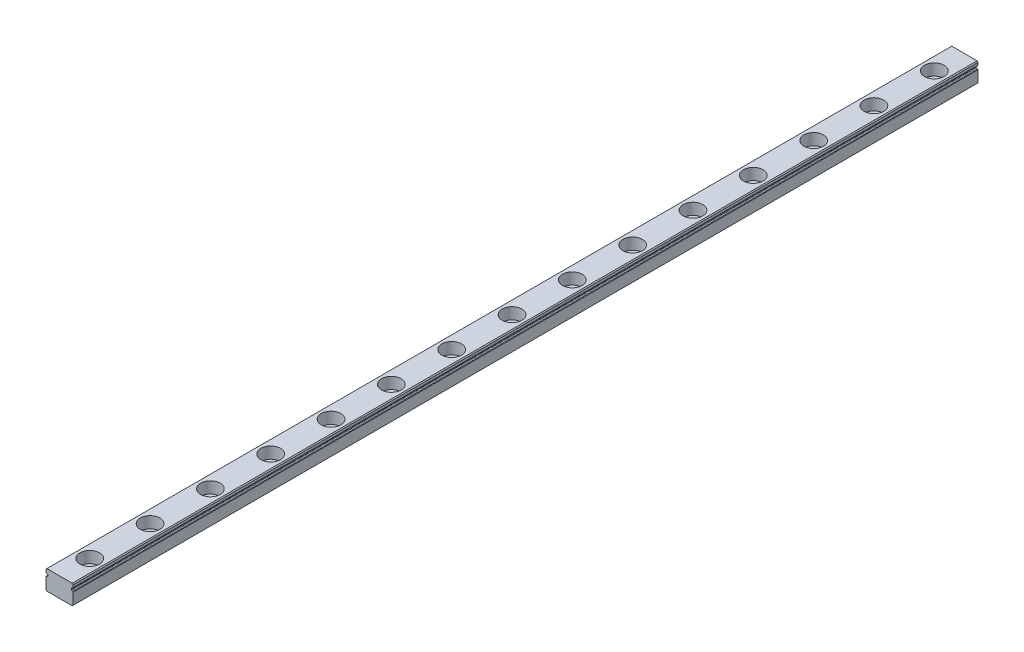
SolidWorks part; units mm, degrees
ref_plane "Plan de face" through (0, 0, 0) normal (0, 0, 1) x (1, 0, 0)
ref_plane "Plan de dessus" through (0, 0, 0) normal (0, 1, 0) x (1, 0, 0)
ref_plane "Plan de droite" through (0, 0, 0) normal (1, 0, 0) x (0, 0, -1)
sketch "Esquisse1" plane through (0, 0, 0) normal (0, 0, 1) x (1, 0, 0)
  line L1 (4.5, -3.25) -> (-4.5, -3.25)
  line L2 (4.5, -3.25) -> (4.5, 3.25)
  line L3 (4.5, 3.25) -> (-4.5, 3.25)
  line L4 (-4.5, -3.25) -> (-4.5, 3.25)
  line L5 (4.5, -3.25) -> (-4.5, 3.25) construction
  line L6 (4.5, 3.25) -> (-4.5, -3.25) construction
  point P0 (0, 0)
  dimension "D1" = 6.5
  dimension "D2" = 9
extrude "Boss.-Extru.1" add sketch "Esquisse1" along normal mid plane 300
sketch "Esquisse2" plane through (0, 0, -150) normal (0, 0, -1) x (-1, 0, 0)
  line L0 (-4.5, 1.9684) -> (-3.9, 1.75)
  line L1 (-4.5, -3.25) -> (-4.5, 3.25) construction
  line L2 (-3.9, 1.75) -> (-3.9, 1.15)
  line L3 (-3.9, 1.15) -> (-4.5, 0.9316)
  line L4 (-4.5, 3.25) -> (4.5, 3.25) construction
  line L5 (-4.5, 1.9684) -> (-4.5, 0.9316)
  dimension "D1" = 1.5
  dimension "D2" = 0.6
  dimension "D3" = 0.6
  dimension "D4" = 110
extrude "Enlèv. mat.-Extru.1" cut sketch "Esquisse2" against normal through all
mirror "Symétrie1" about plane through (0, 0, 0) normal (1, 0, 0) of "Enlèv. mat.-Extru.1"
chamfer "Chanfrein1" distance 0.3 angle 45 4 edges at (-4.5, -3.25, 0) (4.5, -3.25, 0) (-4.5, 3.25, 0) (4.5, 3.25, 0)
fillet "Congé1" radius 0.2 4 edges at (-3.9, 1.15, 0) (-3.9, 1.75, 0) (3.9, 1.75, 0) (3.9, 1.15, 0)
chamfer "Chanfrein2" distance 0.1 angle 45 4 edges at (-4.5, 0.9316, 0) (-4.5, 1.9684, 0) (4.5, 0.9316, 0) (4.5, 1.9684, 0)
hole_wizard "Chambrage pour vis à six pans creux M31" positions "Esquisse4" profile "Esquisse5" counterbore size "M3" standard "ISO" end condition through all
sketch "Esquisse4" plane through (0, 3.25, 0) normal (0, 1, 0) x (1, 0, 0)
  line L0 (0, -55) -> (0, 55) construction
  line L1 (4.2, 150) -> (-4.2, 150) construction
  point P0 (0, 140)
  dimension "D1" = 10
sketch "Esquisse5" plane through (0, 3.25, -140) normal (1, 0, 0) x (0, 0, 1)
  line L0 (0, 0) -> (0, 6.5)
  line L1 (0, 6.5) -> (1.8, 6.5)
  line L3 (1.8, 6.5) -> (1.8, 3.8)
  line L4 (1.8, 3.8) -> (3.25, 3.8)
  line L5 (3.25, 3.8) -> (3.25, 0)
  line L7 (3.25, 0) -> (0, 0)
  line L11 (0, -6.35) -> (0, 107.95) construction
  dimension "Diamètre du perçage jusqu'au prochain" = 3.6
  dimension "Profondeur du perçage jusqu'au prochain" = 6.5
  dimension "Diamètre du chambrage" = 6.5
  dimension "Profondeur du chambrage" = 3.8
pattern_linear "Répétition linéaire1" count 15 spacing 20 along (0, 0, 1) of "Chambrage pour vis à six pans creux M31"
